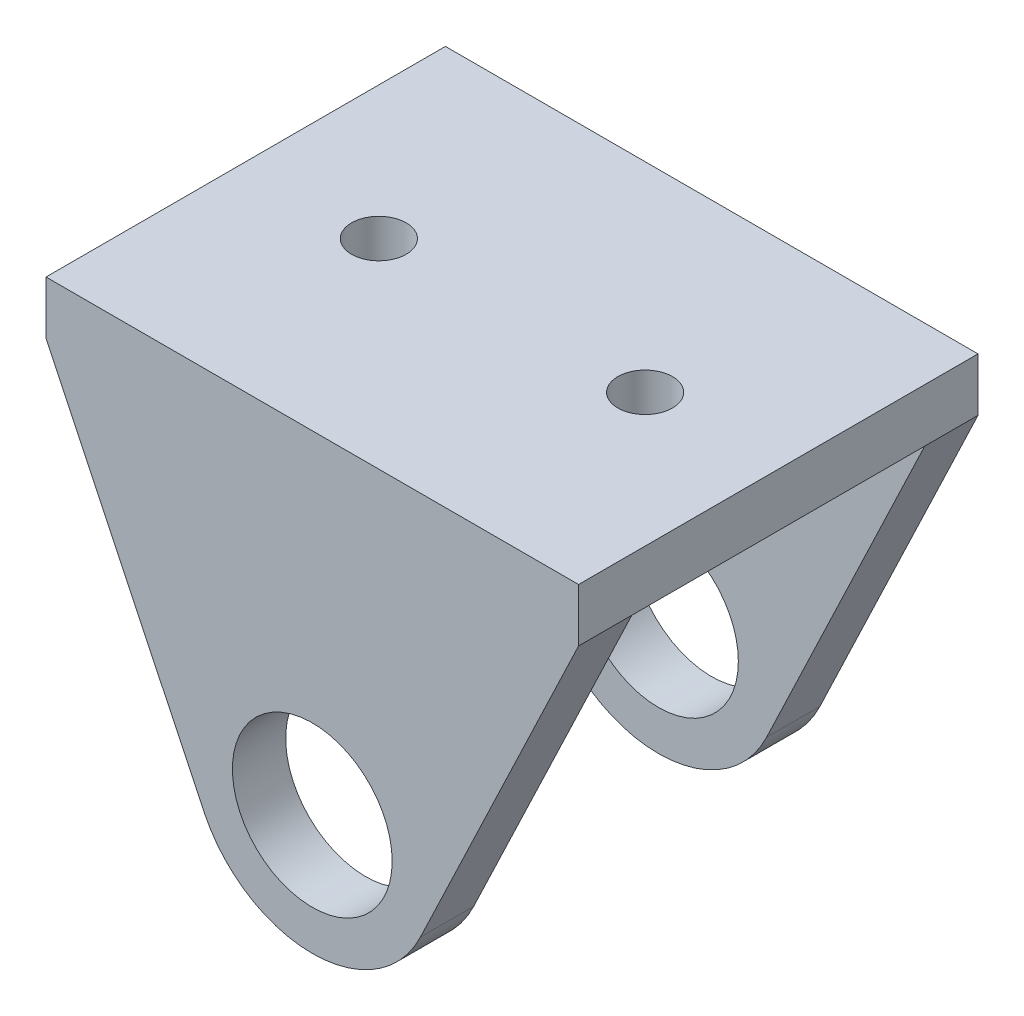
SolidWorks part; units mm, degrees
material "6061 合金"
ref_plane "前视基准面" through (0, 0, 0) normal (0, 0, 1) x (1, 0, 0)
ref_plane "上视基准面" through (0, 0, 0) normal (0, 1, 0) x (1, 0, 0)
ref_plane "右视基准面" through (0, 0, 0) normal (1, 0, 0) x (0, 0, -1)
sketch "草图1" plane through (0, 0, 0) normal (0, 1, 0) x (1, 0, 0)
  line L1 (-20, -10) -> (20, -10)
  line L2 (-20, -10) -> (-20, 10)
  line L3 (-20, 10) -> (20, 10)
  line L4 (20, -10) -> (20, 10)
  line L5 (-20, -10) -> (20, 10) construction
  line L6 (-20, 10) -> (20, -10) construction
  point P0 (0, 0)
  dimension "D1" = 40
  dimension "D2" = 20
extrude "凸台-拉伸1" add sketch "草图1" against normal blind 4
sketch "草图2" plane through (0, 0, 10) normal (0, 0, 1) x (1, 0, 0)
  line L0 (20, -4) -> (20, 0)
  line L1 (20, 0) -> (-20, 0)
  line L2 (-20, 0) -> (20, 0) construction
  line L3 (-20, 0) -> (-20, -4)
  line L4 (-20, -4) -> (-8.1217, -28.8778)
  line L5 (-20, -4) -> (-20, 0) construction
  line L6 (20, -4) -> (8.1217, -28.8778)
  arc A0 (-8.1217, -28.8778) -> (8.1217, -28.8778) centre (0, -25) ccw
  circle A1 centre (0, -25) radius 6
  dimension "D2" = 9
  dimension "D4" = 12
  dimension "D1" = 25
  dimension "D3" = 4
extrude "凸台-拉伸2" add sketch "草图2" along normal blind 5
sketch "草图3" plane through (0, 0, 10) normal (0, 0, -1) x (-1, 0, 0)
  line L0 (20, -4) -> (-20, -4) construction
  line L1 (-20, -39) -> (20, -39)
  line L2 (-20, -39) -> (-20, -4)
  line L3 (-20, -4) -> (20, -4)
  line L4 (20, -39) -> (20, -4)
  point P0 (0, -25)
  dimension "D1" = 35
  dimension "D2" = 40
extrude "切除-拉伸1" cut sketch "草图3" against normal blind 1
fillet "圆角2" [suppressed] radius 3
mirror "镜向1" about plane through (0, 0, 0) normal (0, 0, 1) of "凸台-拉伸2", "切除-拉伸1", "圆角2"
sketch "草图4" [suppressed] plane through (0, 0, 0) normal (0, 1, 0) x (1, 0, 0)
  line L0 (-20, 0) -> (20, 0) construction
  line L1 (-20, 15) -> (-20, -15) construction
  line L2 (20, -15) -> (20, 15) construction
  line L3 (0, 15) -> (0, -15) construction
  line L4 (20, 15) -> (-20, 15) construction
  line L5 (20, -15) -> (-20, -15) construction
  circle A0 centre (-10, 0) radius 2.05
  circle A1 centre (10, 0) radius 2.05
  dimension "D1" = 4.1
  dimension "D2" = 20
extrude "切除-拉伸2" [suppressed] cut sketch "草图4" against normal through all
sketch "草图5" plane through (0, 0, 15) normal (0, 0, 1) x (1, 0, 0)
  line L0 (-36.1153, -14) -> (49963.8847, -14) construction
  line L1 (0, 0) -> (0, 50000) construction
  line L2 (20, 0) -> (-20, 0) construction
  circle A0 centre (-7.5, -14) radius 2.1
  circle A1 centre (7.5, -14) radius 2.1
  point P11 (0, 0)
  dimension "D2" = 4.2
  dimension "D3" = 15
  dimension "D1" = 14
fillet "圆角3" [suppressed] radius 1
sketch "草图6" plane through (0, -4, 0) normal (0, -1, 0) x (1, 0, 0)
  line L0 (0, 0) -> (0, -29.6186) construction
  circle A0 centre (-10, 0) radius 2.05
  circle A1 centre (10, 0) radius 2.05
  dimension "D1" = 20
  dimension "D2" = 4.1
extrude "切除-拉伸3" cut sketch "草图6" against normal blind 10
